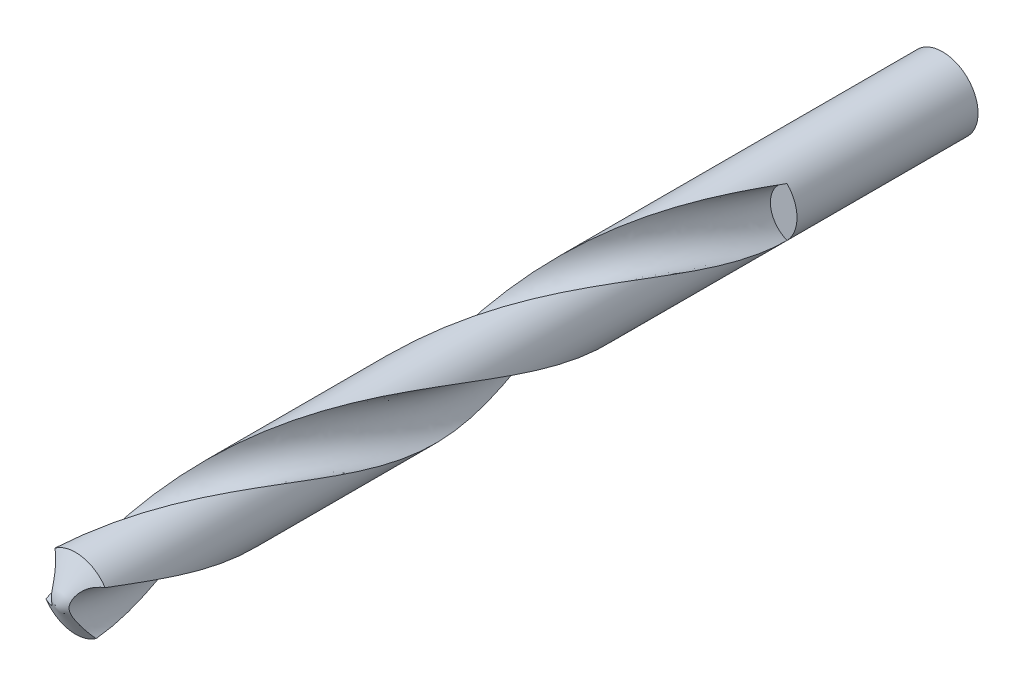
SolidWorks part; units mm, degrees
ref_plane "Front Plane" through (0, 0, 0) normal (0, 0, 1) x (1, 0, 0)
ref_plane "Top Plane" through (0, 0, 0) normal (0, 1, 0) x (1, 0, 0)
ref_plane "Right Plane" through (0, 0, 0) normal (1, 0, 0) x (0, 0, -1)
sketch "Sketch1" plane through (0, 0, 0) normal (0, 0, 1) x (1, 0, 0)
  circle A0 centre (0, 0) radius 2
  dimension "D1" = 4
extrude "Boss-Extrude1" add sketch "Sketch1" along normal blind 60
sketch "Sketch5" plane through (0, 0, 60) normal (0, 0, 1) x (1, 0, 0)
  circle A1 centre (0, 0) radius 2
  circle A2 centre (0, 0) radius 2
  dimension "D1" = 0
curve "Helix/Spiral1" pitch 39.8 height 39.8 turns 1
sketch "Sketch6" plane through (0, 0, 0) normal (0, 1, 0) x (1, 0, 0)
  arc A0 (-2, -20.2) -> (0.5595, -12.8933) centre (9.7091, -20.2) cw
  spline S0 degree 3 poles (1986.385, 117.6637) (215.03, -173.456) (-12.0172, -114.1045) (-1.451, -55.0251) (-0.7853, -52.5375) (0, -50.05) (0.7853, -47.5625) (1.451, -45.075) (1.8959, -42.5875) (2.0521, -40.1) (1.8959, -37.6125) (1.451, -35.125) (0.7853, -32.6375) (0, -30.15) (-0.7853, -27.6625) (-1.451, -25.1749) (-12.0172, 33.9044) (215.0291, 93.2558) (1986.3748, -197.862) knots -4.266231 -4.266231 -4.266231 -4.266231 0.0625 0.125 0.1875 0.25 0.3125 0.375 0.4375 0.5 0.5625 0.625 0.6875 0.75 0.8125 0.875 0.9375 5.266223 5.266223 5.266223 5.266223 only from (-2, -60) to (-2, -20.2) construction
  spline S1 degree 3 poles (-2, -60) (-2, -59.1713) (-1.8959, -57.5123) (-1.451, -55.0251) (-0.7853, -52.5375) (0, -50.05) (0.7853, -47.5625) (1.451, -45.075) (1.8959, -42.5875) (2.0521, -40.1) (1.8959, -37.6125) (1.451, -35.125) (0.7853, -32.6375) (0, -30.15) (-0.7853, -27.6625) (-1.451, -25.1749) (-1.8959, -22.6877) (-2, -21.0287) (-2, -20.2) knots 0 0 0 0 0.0625 0.125 0.1875 0.25 0.3125 0.375 0.4375 0.5 0.5625 0.625 0.6875 0.75 0.8125 0.875 0.9375 1 1 1 1
sketch "Sketch7" plane through (0, 0, 60) normal (0, 0, 1) x (1, 0, 0)
  line L0 (0.5595, 0) -> (-2, 0) construction
  circle A0 centre (-2, 0) radius 1.5
  circle A1 centre (0, 0) radius 2 construction
  dimension "D1" = 3
sweep "Cut-Sweep1" cut profiles "Sketch7" path "Helix/Spiral1"
pattern_circular "CirPattern1" count 2 over 360 about axis through (0, 0, 60) along (0, 0, -1) of "Cut-Sweep1"
sketch "Sketch8" plane through (0, 0, 0) normal (0, 1, 0) x (1, 0, 0)
  line L0 (0, -60) -> (0, -57.8915) construction
  line L1 (-1.4375, -60) -> (1.4375, -60) construction
  line L2 (0, -60) -> (-2.7555, -58.4091)
  line L3 (-2.7555, -58.4091) -> (-2.7555, -61.5433)
  line L4 (-2.7555, -61.5433) -> (0, -61.5433)
  line L5 (0, -61.5433) -> (0, -60)
  dimension "D1" = 60
revolve "Cut-Revolve1" cut sketch "Sketch8" angle 360 about L0
sketch "Sketch9" plane through (0, 0, 0) normal (0, 0, -1) x (-1, 0, 0)
  circle A0 centre (0, 0) radius 2 construction
  circle A1 centre (0, 0) radius 2
extrude "Cut-Extrude1" cut sketch "Sketch9" against normal blind 10
